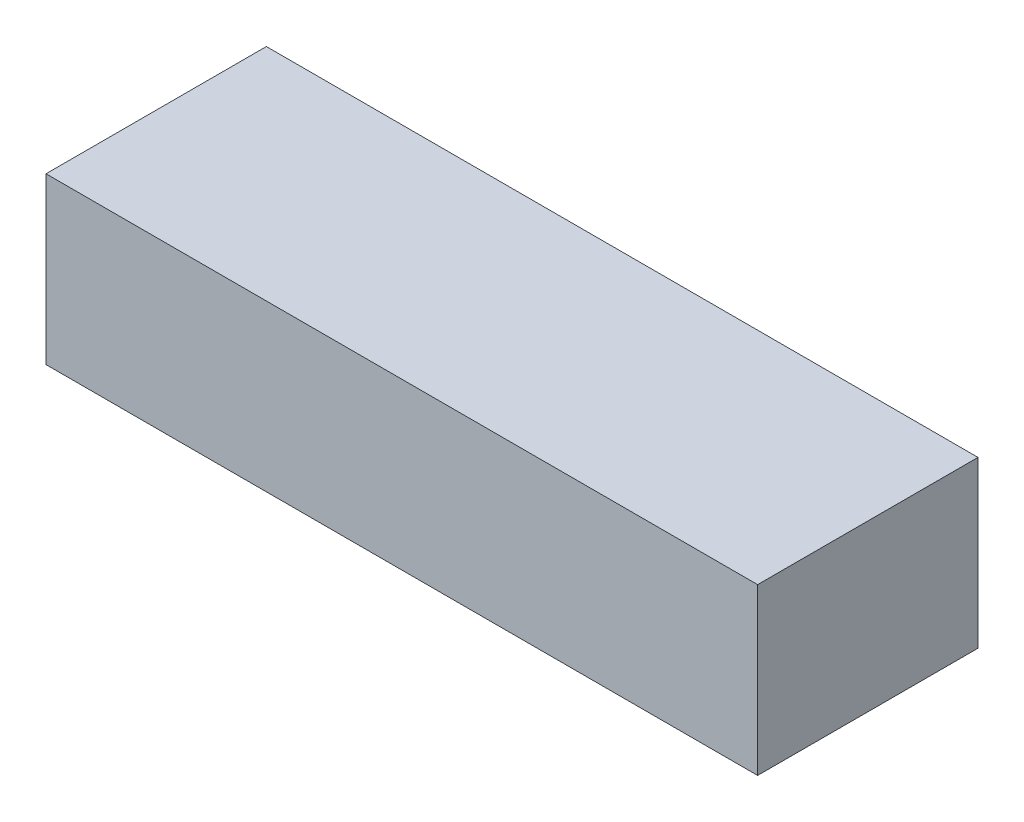
SolidWorks part; units mm, degrees
ref_plane "Front Plane" through (0, 0, 0) normal (0, 0, 1) x (1, 0, 0)
ref_plane "Top Plane" through (0, 0, 0) normal (0, 1, 0) x (1, 0, 0)
ref_plane "Right Plane" through (0, 0, 0) normal (1, 0, 0) x (0, 0, -1)
sketch "Sketch1" plane through (0, 0, 0) normal (0, 1, 0) x (1, 0, 0)
  line L1 (0, 0) -> (155, 0)
  line L2 (0, 0) -> (0, -48)
  line L3 (0, -48) -> (155, -48)
  line L4 (155, 0) -> (155, -48)
  dimension "D1" = 155
  dimension "D2" = 48
extrude "Boss-Extrude1" add sketch "Sketch1" along normal blind 36
sketch "Sketch2" plane through (0, 0, 0) normal (-1, 0, 0) x (0, 0, 1)
  line L0 (0, 36) -> (0, 0) construction
  line L1 (0, 23.5446) -> (11.208, 23.5446)
  line L2 (0, 23.5446) -> (0, 12.8737)
  line L3 (0, 12.8737) -> (11.208, 12.8737)
  line L4 (11.208, 23.5446) -> (11.208, 12.8737)
extrude "Boss-Extrude2" add sketch "Sketch2" along normal blind 10
